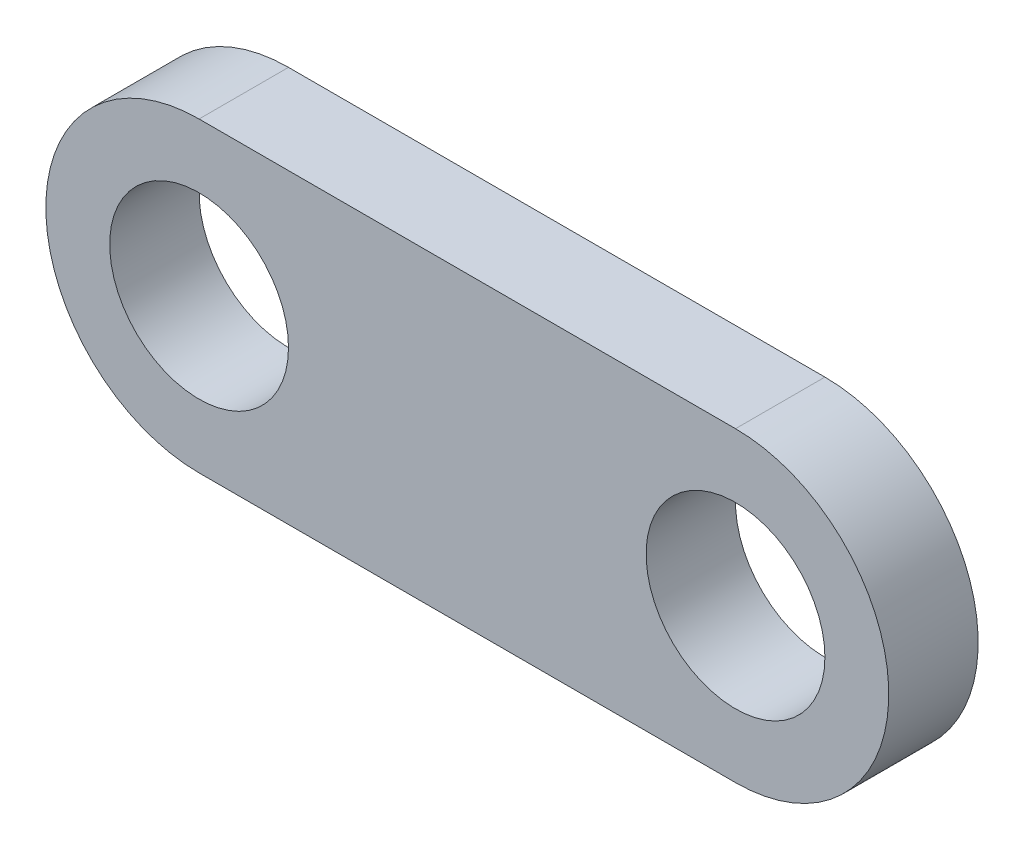
SolidWorks part; units mm, degrees
material "Acier non allié"
ref_plane "Plan de face" through (0, 0, 0) normal (0, 0, 1) x (1, 0, 0)
ref_plane "Plan de dessus" through (0, 0, 0) normal (0, 1, 0) x (1, 0, 0)
ref_plane "Plan de droite" through (0, 0, 0) normal (1, 0, 0) x (0, 0, -1)
ref_plane "Plan4" through (0, 0, 0) normal (0, 0, -1) x (-1, 0, 0)
sketch "Esquisse1" plane through (0, 0, 0) normal (0, 0, -1) x (-1, 0, 0)
  line L0 (0, 12) -> (-42, 12)
  line L1 (-42, -12) -> (0, -12)
  circle A0 centre (-42, 0) radius 7
  circle A1 centre (0, 0) radius 7
  arc A2 (0, -12) -> (0, 12) centre (0, 0) ccw
  arc A3 (-42, 12) -> (-42, -12) centre (-42, 0) ccw
extrude "Extrusion1" add sketch "Esquisse1" against normal blind 7
